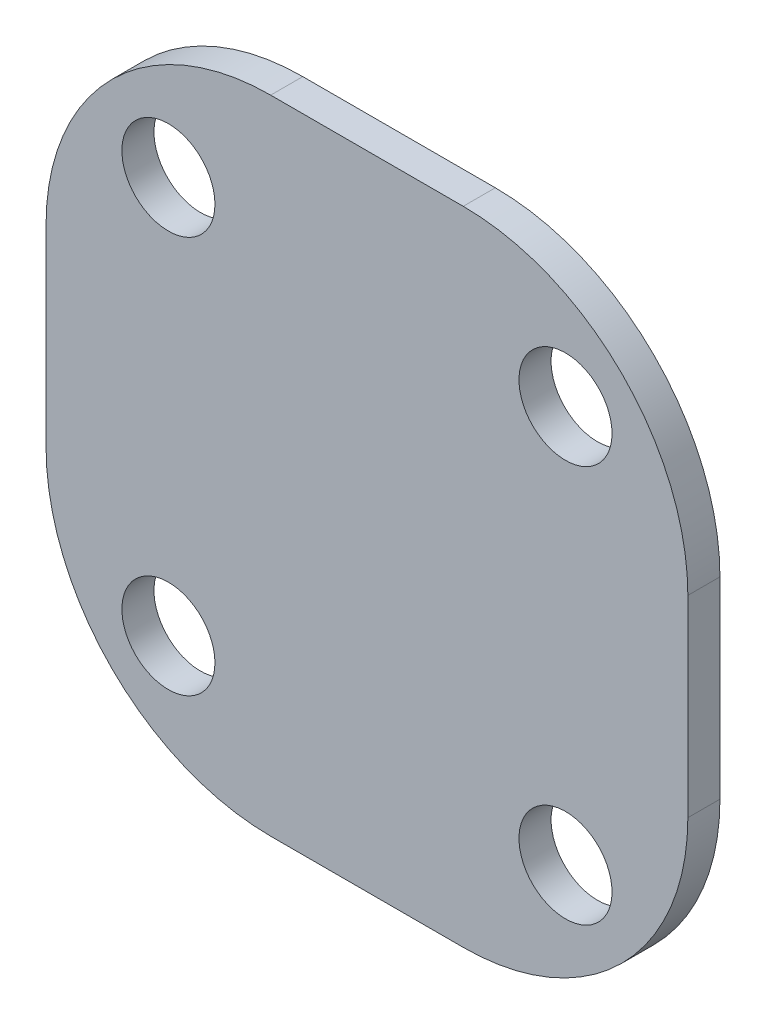
SolidWorks part; units mm, degrees
ref_plane "Front Plane" through (0, 0, 0) normal (0, 0, 1) x (1, 0, 0)
ref_plane "Top Plane" through (0, 0, 0) normal (0, 1, 0) x (1, 0, 0)
ref_plane "Right Plane" through (0, 0, 0) normal (1, 0, 0) x (0, 0, -1)
sketch "Sketch1" plane through (0, 0, 0) normal (0, 0, 1) x (1, 0, 0)
  line L1 (0, 0) -> (25.4, 0)
  line L2 (0, 0) -> (0, -25.4)
  line L3 (0, -25.4) -> (25.4, -25.4)
  line L4 (25.4, 0) -> (25.4, -25.4)
  dimension "D1" = 25.4
  dimension "D2" = 25.4
extrude "Boss-Extrude1" add sketch "Sketch1" along normal blind 1.27
sketch "Sketch8" plane through (0, 0, 1.27) normal (0, 0, 1) x (1, 0, 0)
  circle A0 centre (20.5577, -4.8423) radius 1.8415
  circle A1 centre (20.5577, -4.8423) radius 1.5875
  circle A2 centre (20.5577, -4.8423) radius 1.5875 construction
  circle A3 centre (4.8423, -20.5577) radius 1.5875
  circle A4 centre (4.8423, -20.5577) radius 1.5875 construction
  circle A5 centre (20.5577, -20.5577) radius 1.5875
  circle A6 centre (20.5577, -20.5577) radius 1.5875 construction
  circle A7 centre (4.8423, -4.8423) radius 1.5875
  circle A8 centre (4.8423, -4.8423) radius 1.5875 construction
  circle A9 centre (4.8423, -4.8423) radius 1.8415
  circle A10 centre (4.8423, -20.5577) radius 1.8415
  circle A11 centre (20.5577, -20.5577) radius 1.8415
  arc A24 (12.9928, -6.6746) -> (12.4072, -6.6746) centre (12.7, -12.7) ccw
  arc A25 (12.9928, -6.6746) -> (18.9862, -3.2707) centre (13.1887, -0.0411) ccw
  arc A26 (22.1293, -6.4138) -> (18.9862, -3.2707) centre (20.5577, -4.8423) ccw
  arc A27 (22.1293, -6.4138) -> (18.7254, -12.4072) centre (25.3589, -12.2113) ccw
  arc A28 (18.7254, -12.9928) -> (18.7254, -12.4072) centre (12.7, -12.7) ccw
  arc A29 (18.7254, -12.9928) -> (22.1293, -18.9862) centre (25.3589, -13.1887) ccw
  arc A30 (18.9862, -22.1293) -> (22.1293, -18.9862) centre (20.5577, -20.5577) ccw
  arc A31 (18.9862, -22.1293) -> (12.9928, -18.7254) centre (13.1887, -25.3589) ccw
  arc A32 (12.4072, -18.7254) -> (12.9928, -18.7254) centre (12.7, -12.7) ccw
  arc A33 (12.4072, -18.7254) -> (6.4138, -22.1293) centre (12.2113, -25.3589) ccw
  arc A34 (3.2707, -18.9862) -> (6.4138, -22.1293) centre (4.8423, -20.5577) ccw
  arc A35 (3.2707, -18.9862) -> (6.6746, -12.9928) centre (0.0411, -13.1887) ccw
  arc A36 (6.6746, -12.4072) -> (6.6746, -12.9928) centre (12.7, -12.7) ccw
  arc A37 (6.6746, -12.4072) -> (3.2707, -6.4138) centre (0.0411, -12.2113) ccw
  arc A38 (6.4138, -3.2707) -> (3.2707, -6.4138) centre (4.8423, -4.8423) ccw
  arc A39 (6.4138, -3.2707) -> (12.4072, -6.6746) centre (12.2113, -0.0411) ccw
  arc A40 (12.9928, -6.6746) -> (12.4072, -6.6746) centre (12.7, -12.7) ccw construction
  arc A41 (12.9928, -6.6746) -> (18.9862, -3.2707) centre (13.1887, -0.0411) ccw construction
  arc A42 (22.1293, -6.4138) -> (18.9862, -3.2707) centre (20.5577, -4.8423) ccw construction
  arc A43 (22.1293, -6.4138) -> (18.7254, -12.4072) centre (25.3589, -12.2113) ccw construction
  arc A44 (18.7254, -12.9928) -> (18.7254, -12.4072) centre (12.7, -12.7) ccw construction
  arc A45 (18.7254, -12.9928) -> (22.1293, -18.9862) centre (25.3589, -13.1887) ccw construction
  arc A46 (18.9862, -22.1293) -> (22.1293, -18.9862) centre (20.5577, -20.5577) ccw construction
  arc A47 (18.9862, -22.1293) -> (12.9928, -18.7254) centre (13.1887, -25.3589) ccw construction
  arc A48 (12.4072, -18.7254) -> (12.9928, -18.7254) centre (12.7, -12.7) ccw construction
  arc A49 (12.4072, -18.7254) -> (6.4138, -22.1293) centre (12.2113, -25.3589) ccw construction
  arc A50 (3.2707, -18.9862) -> (6.4138, -22.1293) centre (4.8423, -20.5577) ccw construction
  arc A51 (3.2707, -18.9862) -> (6.6746, -12.9928) centre (0.0411, -13.1887) ccw construction
  arc A52 (6.6746, -12.4072) -> (6.6746, -12.9928) centre (12.7, -12.7) ccw construction
  arc A53 (6.6746, -12.4072) -> (3.2707, -6.4138) centre (0.0411, -12.2113) ccw construction
  arc A54 (6.4138, -3.2707) -> (3.2707, -6.4138) centre (4.8423, -4.8423) ccw construction
  arc A55 (6.4138, -3.2707) -> (12.4072, -6.6746) centre (12.2113, -0.0411) ccw construction
  dimension "D1" = 0
  dimension "D2" = 0
  dimension "D3" = 0
  dimension "D4" = 0
  dimension "D5" = 0
  dimension "D6" = 0.254
extrude "Mounting Holes for Motor" cut sketch "Sketch8" against normal up to next
fillet "Fillet2" radius 8.89 4 edges at (0, -25.4, 0.635) (25.4, -25.4, 0.635) (0, 0, 0.635) (25.4, 0, 0.635)
